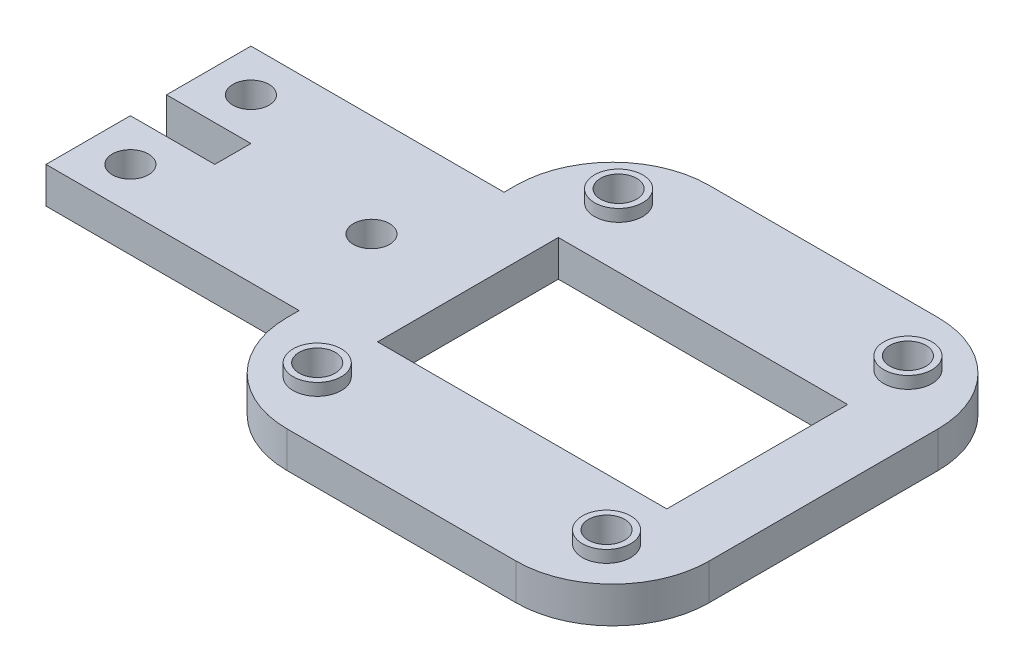
SolidWorks part; units mm, degrees
ref_plane "前视基准面" through (0, 0, 0) normal (0, 0, 1) x (1, 0, 0)
ref_plane "上视基准面" through (0, 0, 0) normal (0, 1, 0) x (1, 0, 0)
ref_plane "右视基准面" through (0, 0, 0) normal (1, 0, 0) x (0, 0, -1)
other "Configuration Table"
sketch "草图1" plane through (0, 0, 0) normal (0, 1, 0) x (1, 0, 0)
  line L0 (-4, 0) -> (-2.5, 0)
  line L1 (-17.5, 5) -> (-15.4412, 5) construction
  line L2 (-17.5, 5) -> (-17.5, -5) construction
  line L3 (-17.5, -5) -> (-15.4412, -5) construction
  line L4 (17.5, 5) -> (17.5, -5) construction
  line L5 (-17.5, 5) -> (-15.6579, 4.4737) construction
  line L6 (-17.5, -5) -> (-15.6579, -4.4737) construction
  line L7 (5.5, 12.5) -> (29.5, 12.5) construction
  line L8 (5.5, 12.5) -> (5.5, -12.5) construction
  line L9 (5.5, -12.5) -> (29.5, -12.5) construction
  line L10 (29.5, 12.5) -> (29.5, -12.5) construction
  line L11 (5.5, 12.5) -> (29.5, -12.5) construction
  line L12 (5.5, -12.5) -> (29.5, 12.5) construction
  line L13 (5.5, 7.5) -> (29.5, 7.5)
  line L14 (5.5, 7.5) -> (5.5, -7.5)
  line L15 (5.5, -7.5) -> (29.5, -7.5)
  line L16 (29.5, 7.5) -> (29.5, -7.5)
  line L17 (5.5, 7.5) -> (29.5, -7.5) construction
  line L18 (5.5, -7.5) -> (29.5, 7.5) construction
  line L19 (0, 17.5) -> (35, 17.5)
  line L20 (0, 17.5) -> (0, 8.5)
  line L21 (0, -17.5) -> (35, -17.5)
  line L22 (35, 17.5) -> (35, -17.5)
  line L23 (0, 17.5) -> (35, -17.5) construction
  line L24 (0, -17.5) -> (35, 17.5) construction
  line L25 (-14, 8.5) -> (0, 8.5)
  line L26 (-21, 8.5) -> (-14, 8.5)
  line L27 (-21, 8.5) -> (-21, -8.5)
  line L28 (-21, -8.5) -> (-14, -8.5)
  line L30 (-21, 8.5) -> (-14, -8.5) construction
  line L31 (-21, -8.5) -> (-14, 8.5) construction
  line L32 (-14, -8.5) -> (0, -8.5)
  line L33 (0, -8.5) -> (0, -17.5)
  line L34 (5.5, -1.5714) -> (17.5, -5) construction
  line L35 (5.5, 1.5714) -> (17.5, 5) construction
  line L36 (5.5, 5) -> (17.5, 5) construction
  line L37 (5.5, -5) -> (17.5, -5) construction
  line L38 (-3.5935, 1.0267) -> (-1.0291, 0.294) construction
  line L39 (-3.5935, -1.0267) -> (-1.0291, -0.294) construction
  circle A0 centre (-17.5, 5) radius 1.5
  circle A1 centre (-17.5, -5) radius 1.5
  circle A2 centre (5.5, 12.5) radius 1.5
  circle A3 centre (29.5, 12.5) radius 1.5
  circle A4 centre (5.5, -12.5) radius 1.5
  circle A5 centre (29.5, -12.5) radius 1.5
  circle A6 centre (-2.5, 0) radius 1.5
  point P0 (0, 0)
  point P8 (17.5, 0)
  point P17 (17.5, 0)
  point P22 (17.5, 0)
  dimension "D2" = 3
  dimension "D3" = 3
  dimension "D7" = 3
  dimension "D8" = 3
  dimension "D9" = 3
  dimension "D10" = 3
  dimension "D14" = 3
  dimension "D1" = 10
  dimension "D4" = 35
  dimension "D5" = 25
  dimension "D6" = 24
  dimension "D11" = 15
  dimension "D12" = 24
  dimension "D15" = 7
  dimension "D16" = 17
  dimension "D17" = 35
  dimension "D18" = 35
extrude "凸台-拉伸1" add sketch "草图1" along normal blind 3 contours L32 L33 L21 L22 L19 L20 L25 L26 L27 L28 A6 A5 A4 A3 A2 A1 A0 L13 L16 L15 L14
sketch "草图2" plane through (0, 3, 0) normal (0, 1, 0) x (1, 0, 0)
  circle A0 centre (5.5, 12.5) radius 1.5
  circle A1 centre (29.5, 12.5) radius 1.5
  circle A2 centre (5.5, -12.5) radius 1.5
  circle A3 centre (29.5, -12.5) radius 1.5
  circle A4 centre (5.5, 12.5) radius 2
  circle A5 centre (29.5, 12.5) radius 2
  circle A6 centre (29.5, -12.5) radius 2
  circle A7 centre (5.5, -12.5) radius 2
  dimension "D1" = 4
  dimension "D2" = 4
  dimension "D3" = 4
  dimension "D4" = 4
extrude "凸台-拉伸2" add sketch "草图2" along normal blind 1
sketch "草图3" plane through (0, 3, 0) normal (0, 1, 0) x (1, 0, 0)
  line L0 (-21, 0) -> (-17.5, 0) construction
  line L1 (-21, 8.5) -> (-21, -8.5) construction
  line L3 (-14, 1.5) -> (-21, 1.5)
  line L4 (-14, 1.5) -> (-14, -1.5)
  line L5 (-14, -1.5) -> (-21, -1.5)
  line L6 (-21, 1.5) -> (-21, -1.5)
  line L7 (-14, 1.5) -> (-21, -1.5) construction
  line L8 (-14, -1.5) -> (-21, 1.5) construction
  dimension "D1" = 3.5
  dimension "D2" = 3
extrude "切除-拉伸1" cut sketch "草图3" against normal up to next
fillet "圆角1" radius 8 4 edges at (0, 1.5, -17.5) (0, 1.5, 17.5) (35, 1.5, 17.5) (35, 1.5, -17.5)
